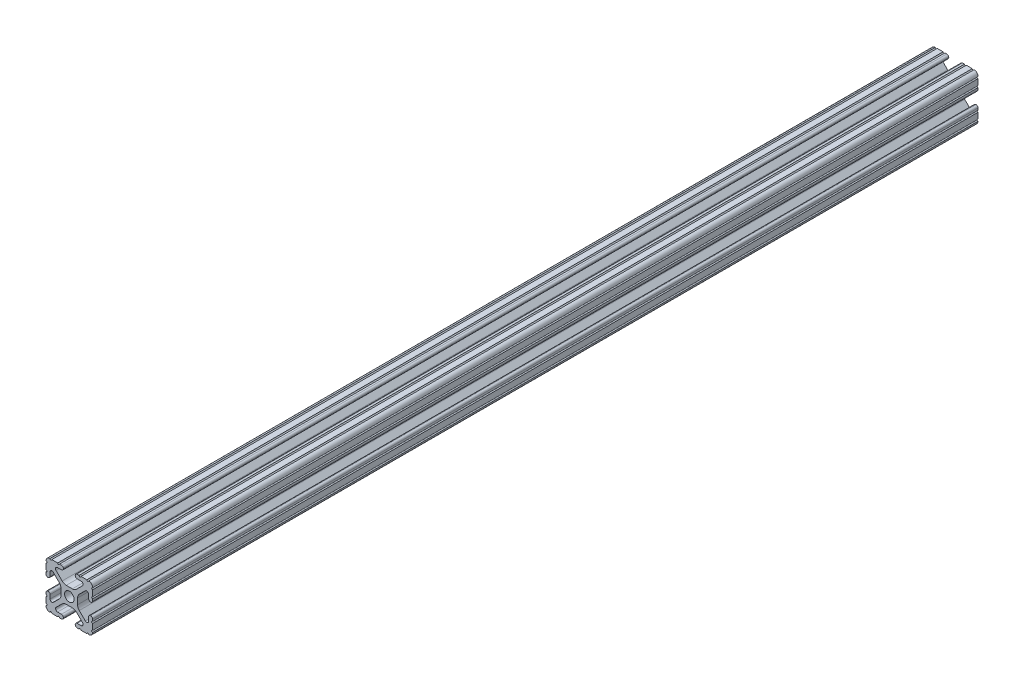
SolidWorks part; units mm, degrees
material "6105-T5 Aluminum"
ref_plane "Front Plane" through (0, 0, 0) normal (0, 0, 1) x (1, 0, 0)
ref_plane "Top Plane" through (0, 0, 0) normal (0, 1, 0) x (1, 0, 0)
ref_plane "Right Plane" through (0, 0, 0) normal (1, 0, 0) x (0, 0, -1)
sketch "Sketch1" plane through (0, 0, 0) normal (0, 0, 1) x (1, 0, 0)
  line L0 (-7.207, 8.7244) -> (-3.8983, 5.4232)
  line L1 (-4.2875, 10.4902) -> (-6.4768, 10.4902)
  line L2 (-3.2385, 11.651) -> (-3.2385, 11.5392)
  line L3 (-5.3171, 12.7) -> (-4.2875, 12.7)
  line L4 (0, 13.4005) -> (0, -14.8534) construction
  line L5 (12.7, 0) -> (-13.9989, 0) construction
  line L6 (-9.5504, 12.7) -> (-6.3331, 12.7)
  line L7 (-12.7, 6.3331) -> (-12.7, 9.5504)
  line L8 (-12.7, 4.2875) -> (-12.7, 5.3171)
  line L9 (-11.5392, 3.2385) -> (-11.651, 3.2385)
  line L10 (-10.4902, 6.4021) -> (-10.4902, 4.2875)
  line L11 (-5.441, 3.8408) -> (-8.7371, 7.1294)
  line L12 (-4.5085, -1.5932) -> (-4.5085, 1.5932)
  line L13 (-1.7093, -4.4958) -> (1.7093, -4.4958)
  line L14 (3.9523, -5.4237) -> (7.1797, -8.6452)
  line L15 (6.4164, -10.4902) -> (4.2875, -10.4902)
  line L16 (3.2385, -11.5392) -> (3.2385, -11.651)
  line L17 (4.2875, -12.7) -> (5.3171, -12.7)
  line L18 (6.3331, -12.7) -> (9.5504, -12.7)
  line L19 (12.7, -9.5504) -> (12.7, -6.3331)
  line L20 (12.7, -5.3171) -> (12.7, -4.2875)
  line L21 (11.651, -3.2385) -> (11.5392, -3.2385)
  line L22 (10.4902, -4.2875) -> (10.4902, -6.4021)
  line L23 (8.7371, -7.1294) -> (5.441, -3.8408)
  line L24 (4.5085, -1.5932) -> (4.5085, 1.5932)
  line L25 (5.441, 3.8408) -> (8.7371, 7.1294)
  line L26 (10.4902, 6.4021) -> (10.4902, 4.2875)
  line L27 (11.5392, 3.2385) -> (11.651, 3.2385)
  line L28 (12.7, 4.2875) -> (12.7, 5.3171)
  line L29 (12.7, 6.3331) -> (12.7, 9.5504)
  line L30 (9.5504, 12.7) -> (6.3331, 12.7)
  line L31 (5.3171, 12.7) -> (4.2875, 12.7)
  line L32 (3.2385, 11.651) -> (3.2385, 11.5392)
  line L33 (4.2875, 10.4902) -> (6.4768, 10.4902)
  line L34 (7.207, 8.7244) -> (3.8983, 5.4232)
  line L35 (1.6558, 4.4958) -> (-1.6558, 4.4958)
  line L36 (-8.7371, -7.1294) -> (-5.441, -3.8408)
  line L37 (-10.4902, -4.2875) -> (-10.4902, -6.4021)
  line L38 (-11.651, -3.2385) -> (-11.5392, -3.2385)
  line L39 (-12.7, -5.3171) -> (-12.7, -4.2875)
  line L40 (-12.7, -9.5504) -> (-12.7, -6.3331)
  line L41 (-6.3331, -12.7) -> (-9.5504, -12.7)
  line L42 (-4.2875, -12.7) -> (-5.3171, -12.7)
  line L43 (-3.2385, -11.5392) -> (-3.2385, -11.651)
  line L44 (-6.4164, -10.4902) -> (-4.2875, -10.4902)
  line L45 (-3.9523, -5.4237) -> (-7.1797, -8.6452)
  arc A0 (-7.207, 8.7244) -> (-6.4768, 10.4902) centre (-6.4768, 9.4563) cw
  arc A1 (-3.2385, 11.5392) -> (-4.2875, 10.4902) centre (-4.2875, 11.5392) cw
  arc A2 (-4.2875, 12.7) -> (-3.2385, 11.651) centre (-4.2875, 11.651) cw
  arc A3 (-5.3171, 12.7) -> (-6.3331, 12.7) centre (-5.8251, 12.7) cw
  arc A4 (-9.5504, 12.7) -> (-10.5664, 12.6998) centre (-10.0584, 12.7) cw
  arc A5 (-12.6998, 10.5664) -> (-10.5664, 12.6998) centre (-10.5918, 10.5918) cw
  arc A6 (-12.6998, 10.5664) -> (-12.7, 9.5504) centre (-12.7, 10.0584) cw
  arc A7 (-12.7, 6.3331) -> (-12.7, 5.3171) centre (-12.7, 5.8251) cw
  arc A8 (-11.651, 3.2385) -> (-12.7, 4.2875) centre (-11.651, 4.2875) cw
  arc A9 (-10.4902, 4.2875) -> (-11.5392, 3.2385) centre (-11.5392, 4.2875) cw
  circle A10 centre (0, 0) radius 2.6035
  arc A11 (-10.4902, 6.4021) -> (-8.7371, 7.1294) centre (-9.4628, 6.4021) cw
  arc A12 (-5.441, 3.8408) -> (-4.5085, 1.5932) centre (-7.6835, 1.5932) cw
  arc A13 (-4.5085, -1.5932) -> (-5.441, -3.8408) centre (-7.6835, -1.5932) cw
  arc A14 (-8.7371, -7.1294) -> (-10.4902, -6.4021) centre (-9.4628, -6.4021) cw
  arc A15 (-1.7093, -4.4958) -> (-3.9523, -5.4237) centre (-1.7093, -7.6708) ccw
  arc A16 (3.9523, -5.4237) -> (1.7093, -4.4958) centre (1.7093, -7.6708) ccw
  arc A17 (6.4164, -10.4902) -> (7.1797, -8.6452) centre (6.4164, -9.4098) ccw
  arc A18 (4.2875, -10.4902) -> (3.2385, -11.5392) centre (4.2875, -11.5392) ccw
  arc A19 (3.2385, -11.651) -> (4.2875, -12.7) centre (4.2875, -11.651) ccw
  arc A20 (6.3331, -12.7) -> (5.3171, -12.7) centre (5.8251, -12.7) ccw
  arc A21 (10.5664, -12.6998) -> (9.5504, -12.7) centre (10.0584, -12.7) ccw
  arc A22 (10.5664, -12.6998) -> (12.6998, -10.5664) centre (10.5918, -10.5918) ccw
  arc A23 (12.7, -9.5504) -> (12.6998, -10.5664) centre (12.7, -10.0584) ccw
  arc A24 (12.7, -5.3171) -> (12.7, -6.3331) centre (12.7, -5.8251) ccw
  arc A25 (12.7, -4.2875) -> (11.651, -3.2385) centre (11.651, -4.2875) ccw
  arc A26 (11.5392, -3.2385) -> (10.4902, -4.2875) centre (11.5392, -4.2875) ccw
  arc A27 (8.7371, -7.1294) -> (10.4902, -6.4021) centre (9.4628, -6.4021) ccw
  arc A28 (4.5085, -1.5932) -> (5.441, -3.8408) centre (7.6835, -1.5932) ccw
  arc A29 (5.441, 3.8408) -> (4.5085, 1.5932) centre (7.6835, 1.5932) ccw
  arc A30 (10.4902, 6.4021) -> (8.7371, 7.1294) centre (9.4628, 6.4021) ccw
  arc A31 (10.4902, 4.2875) -> (11.5392, 3.2385) centre (11.5392, 4.2875) ccw
  arc A32 (11.651, 3.2385) -> (12.7, 4.2875) centre (11.651, 4.2875) ccw
  arc A33 (12.7, 6.3331) -> (12.7, 5.3171) centre (12.7, 5.8251) ccw
  arc A34 (12.6998, 10.5664) -> (12.7, 9.5504) centre (12.7, 10.0584) ccw
  arc A35 (12.6998, 10.5664) -> (10.5664, 12.6998) centre (10.5918, 10.5918) ccw
  arc A36 (9.5504, 12.7) -> (10.5664, 12.6998) centre (10.0584, 12.7) ccw
  arc A37 (5.3171, 12.7) -> (6.3331, 12.7) centre (5.8251, 12.7) ccw
  arc A38 (4.2875, 12.7) -> (3.2385, 11.651) centre (4.2875, 11.651) ccw
  arc A39 (3.2385, 11.5392) -> (4.2875, 10.4902) centre (4.2875, 11.5392) ccw
  arc A40 (7.207, 8.7244) -> (6.4768, 10.4902) centre (6.4768, 9.4563) ccw
  arc A41 (1.6558, 4.4958) -> (3.8983, 5.4232) centre (1.6558, 7.6708) ccw
  arc A42 (-1.6558, 4.4958) -> (-3.8983, 5.4232) centre (-1.6558, 7.6708) cw
  arc A43 (-11.5392, -3.2385) -> (-10.4902, -4.2875) centre (-11.5392, -4.2875) cw
  arc A44 (-12.7, -4.2875) -> (-11.651, -3.2385) centre (-11.651, -4.2875) cw
  arc A45 (-12.7, -5.3171) -> (-12.7, -6.3331) centre (-12.7, -5.8251) cw
  arc A46 (-12.7, -9.5504) -> (-12.6998, -10.5664) centre (-12.7, -10.0584) cw
  arc A47 (-10.5664, -12.6998) -> (-12.6998, -10.5664) centre (-10.5918, -10.5918) cw
  arc A48 (-10.5664, -12.6998) -> (-9.5504, -12.7) centre (-10.0584, -12.7) cw
  arc A49 (-6.3331, -12.7) -> (-5.3171, -12.7) centre (-5.8251, -12.7) cw
  arc A50 (-3.2385, -11.651) -> (-4.2875, -12.7) centre (-4.2875, -11.651) cw
  arc A51 (-4.2875, -10.4902) -> (-3.2385, -11.5392) centre (-4.2875, -11.5392) cw
  arc A52 (-6.4164, -10.4902) -> (-7.1797, -8.6452) centre (-6.4164, -9.4098) cw
  dimension "D1" = 5.207
  dimension "D9" = 14.859
  dimension "D2" = 25.4
  dimension "D3" = 12.7
  dimension "D4" = 6.477
  dimension "D5" = 8.2042
  dimension "D6" = 9.017
  dimension "D8" = 2.2098
  dimension "D10" = 2.2098
extrude "Extrude1" add sketch "Sketch1" against normal blind 482.6
